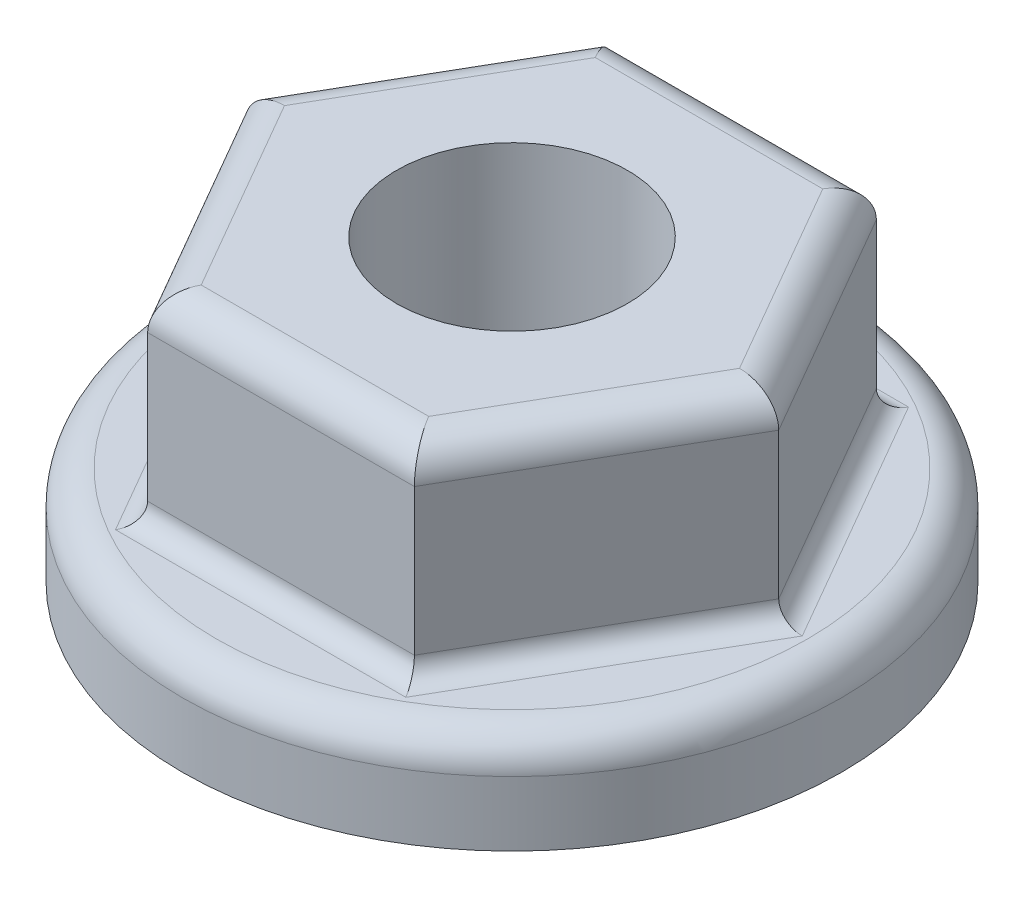
SolidWorks part; units mm, degrees
ref_plane "前视基准面" through (0, 0, 0) normal (0, 0, 1) x (1, 0, 0)
ref_plane "上视基准面" through (0, 0, 0) normal (0, 1, 0) x (1, 0, 0)
ref_plane "右视基准面" through (0, 0, 0) normal (1, 0, 0) x (0, 0, -1)
other "Configuration Table"
sketch "草图1" plane through (0, 0, 0) normal (0, 1, 0) x (1, 0, 0)
  circle A0 centre (33.1829, 0) radius 4.85
extrude "凸台-拉伸1" add sketch "草图1" along normal blind 1.45
sketch "草图2" plane through (0, 1.45, 0) normal (0, 1, 0) x (1, 0, 0)
  line L1 (37.1089, 0) -> (35.1459, 3.4)
  line L2 (35.1459, 3.4) -> (31.2199, 3.4)
  line L3 (31.2199, 3.4) -> (29.2569, 0)
  line L4 (29.2569, 0) -> (31.2199, -3.4)
  line L5 (31.2199, -3.4) -> (35.1459, -3.4)
  line L6 (35.1459, -3.4) -> (37.1089, 0)
  circle A0 centre (33.1829, 0) radius 3.4 construction
extrude "凸台-拉伸2" add sketch "草图2" along normal blind 2.95
sketch "草图3" plane through (0, 4.4, 0) normal (0, 1, 0) x (1, 0, 0)
  circle A0 centre (33.1829, 0) radius 1.7
extrude "切除-拉伸1" cut sketch "草图3" against normal through all
fillet "圆角1" radius 0.5 6 edges at (36.1274, 4.4, 1.7) (36.1274, 4.4, -1.7) (33.1829, 4.4, -3.4) (30.2384, 4.4, -1.7) (30.2384, 4.4, 1.7) (33.1829, 4.4, 3.4)
fillet "圆角2" radius 0.5 1 edges at (33.1829, 1.45, 4.85)
fillet "圆角3" radius 0.3 6 edges at (36.1274, 1.45, -1.7) (36.1274, 1.45, 1.7) (33.1829, 1.45, 3.4) (30.2384, 1.45, 1.7) (33.1829, 1.45, -3.4) (30.2384, 1.45, -1.7)
